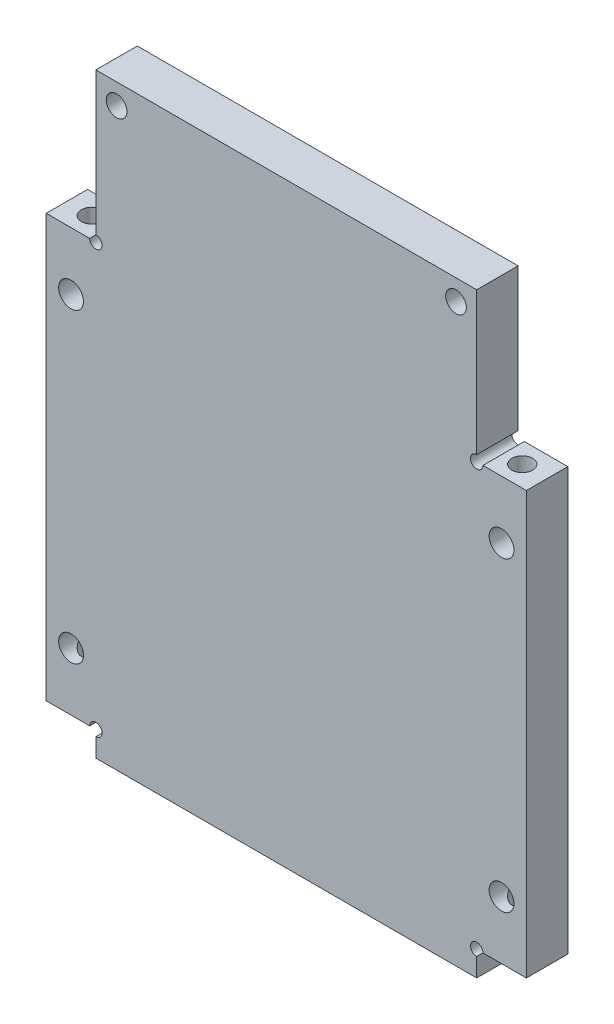
SolidWorks part; units mm, degrees
material "5052-O"
ref_plane "正面" through (0, 0, 0) normal (0, 0, 1) x (1, 0, 0)
ref_plane "平面" through (0, 0, 0) normal (0, 1, 0) x (1, 0, 0)
ref_plane "右側面" through (0, 0, 0) normal (1, 0, 0) x (0, 0, -1)
sketch "ｽｹｯﾁ1" plane through (0, 0, 0) normal (0, 0, 1) x (1, 0, 0)
  line L0 (-29, 51) -> (-29, 0)
  line L1 (-29, 0) -> (-23, 0)
  line L2 (29, 0) -> (29, 51)
  line L3 (-29, 51) -> (-23, 51)
  line L4 (-23, 51) -> (-23, 69)
  line L7 (-23, 69) -> (23, 69)
  line L10 (23, 69) -> (23, 51)
  line L11 (23, 51) -> (29, 51)
  line L12 (-23, 0) -> (-23, -3)
  line L13 (-23, -3) -> (23, -3)
  line L14 (23, -3) -> (23, 0)
  line L15 (23, 0) -> (29, 0)
  line L16 (0, 0) -> (0, -3) construction
  dimension "D1" = 58
  dimension "D2" = 51
  dimension "D3" = 6
  dimension "D4" = 18
  dimension "D6" = 3
extrude "ﾎﾞｽ - 押し出し1" add sketch "ｽｹｯﾁ1" along normal blind 5
sketch "ｽｹｯﾁ3" plane through (0, 51, 0) normal (0, 1, 0) x (1, 0, 0)
  line L0 (-29, -2.5) -> (-23, -2.5) construction
  line L1 (-29, -5) -> (-29, 0) construction
  line L3 (-23, -5) -> (-23, 0) construction
  line L5 (23, -2.5) -> (29, -2.5) construction
  line L6 (29, -5) -> (29, 0) construction
  line L7 (23, -5) -> (23, 0) construction
  circle A0 centre (-26, -2.5) radius 1.25
  circle A1 centre (26, -2.5) radius 1.25
  dimension "D1" = 2.5
extrude "ｶｯﾄ - 押し出し2" cut sketch "ｽｹｯﾁ3" against normal blind 7.5
ref_plane "平面1" through (0, 25.5, 0) normal (0, 1, 0) x (1, 0, 0)
mirror "ﾐﾗｰ1" about plane through (0, 25.5, 0) normal (0, 1, 0) of "ｶｯﾄ - 押し出し2"
sketch "ｽｹｯﾁ4" plane through (0, 0, 0) normal (0, 0, -1) x (-1, 0, 0)
  line L0 (-23, 66.5) -> (23, 66.5) construction
  line L3 (-23, 69) -> (23, 69) construction
  line L4 (-23, 51) -> (-23, 69) construction
  line L5 (23, 69) -> (23, 51) construction
  circle A0 centre (-20.5, 66.5) radius 1.25
  circle A1 centre (20.5, 66.5) radius 1.25
  dimension "D2" = 2.5
  dimension "D3" = 2.5
  dimension "D4" = 2.5
  dimension "D1" = 2.5
extrude "ｶｯﾄ - 押し出し3" cut sketch "ｽｹｯﾁ4" against normal through all
sketch "ｽｹｯﾁ5" plane through (0, 0, 0) normal (0, 0, -1) x (-1, 0, 0)
  circle A2 centre (-23, 0) radius 0.75
  circle A5 centre (23, 0) radius 0.75
  circle A6 centre (-23, 51) radius 0.75
  circle A7 centre (23, 51) radius 0.75
  dimension "D1" = 1.5
extrude "ｶｯﾄ - 押し出し4" cut sketch "ｽｹｯﾁ5" against normal through all
sketch "ｽｹｯﾁ6" plane through (0, 0, 0) normal (0, 0, -1) x (-1, 0, 0)
  line L0 (-26, 0) -> (-26, 51) construction
  line L1 (-23.75, 0) -> (-29, 0) construction
  line L2 (-29, 51) -> (-23.75, 51) construction
  line L3 (-29, 0) -> (-29, 51) construction
  line L4 (2.75, 25.5) -> (-2.75, 25.5) construction
  line L5 (0, 0) -> (0, 69) construction
  line L6 (-23, 69) -> (23, 69) construction
  line L7 (26, 0) -> (26, 51) construction
  circle A0 centre (-26, 44) radius 1.5
  circle A1 centre (-26, 7) radius 1.5
  circle A2 centre (26, 7) radius 1.5
  circle A3 centre (26, 44) radius 1.5
  dimension "D2" = 7
  dimension "D3" = 3
  dimension "D1" = 3
extrude "ｶｯﾄ - 押し出し5" cut sketch "ｽｹｯﾁ6" against normal through all
